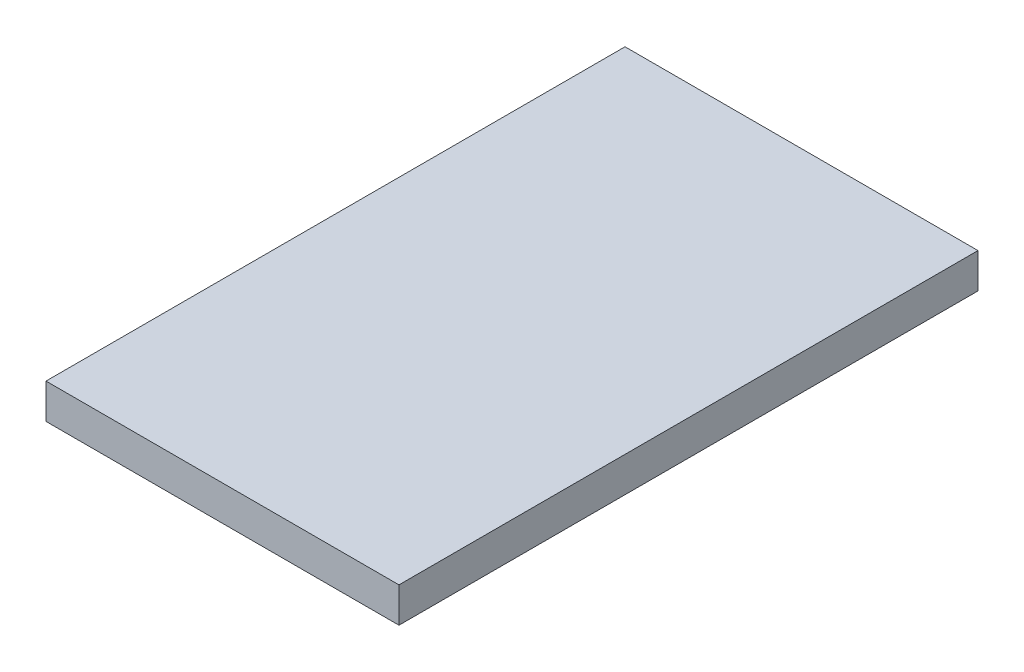
SolidWorks part; units mm, degrees
ref_plane "Front Plane" through (0, 0, 0) normal (0, 0, 1) x (1, 0, 0)
ref_plane "Top Plane" through (0, 0, 0) normal (0, 1, 0) x (1, 0, 0)
ref_plane "Right Plane" through (0, 0, 0) normal (1, 0, 0) x (0, 0, -1)
sketch "Sketch1" plane through (0, 0, 0) normal (0, 1, 0) x (1, 0, 0)
  line L1 (0, 0) -> (120, 0)
  line L2 (0, 0) -> (0, 196.85)
  line L3 (0, 196.85) -> (120, 196.85)
  line L4 (120, 0) -> (120, 196.85)
  dimension "D1" = 120
  dimension "D2" = 196.85
extrude "Boss-Extrude1" add sketch "Sketch1" along normal blind 11.8872
